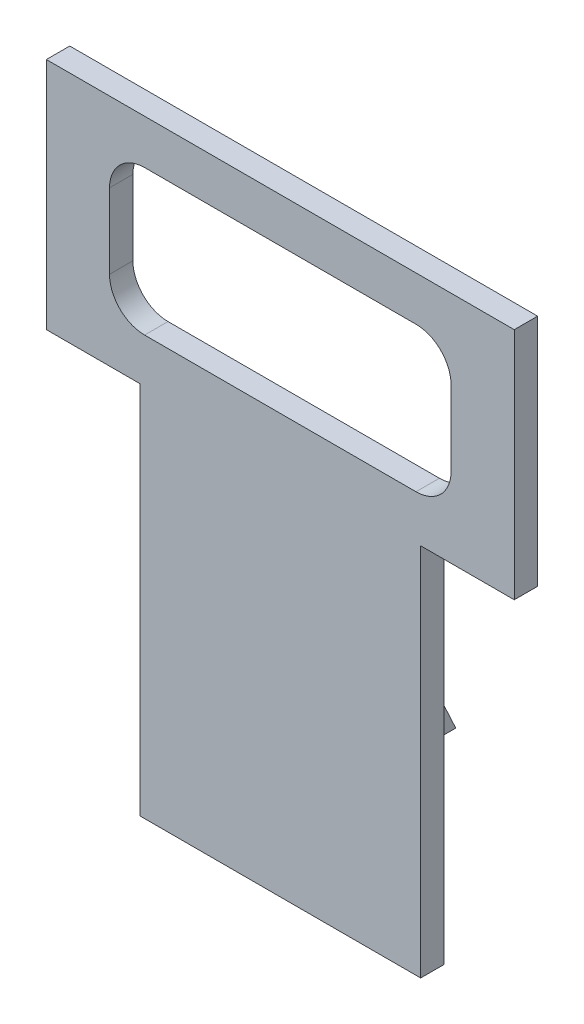
SolidWorks part; units mm, degrees
material "PVC 0.007 Plasticized"
ref_plane "Front Plane" through (0, 0, 0) normal (0, 0, 1) x (1, 0, 0)
ref_plane "Top Plane" through (0, 0, 0) normal (0, 1, 0) x (1, 0, 0)
ref_plane "Right Plane" through (0, 0, 0) normal (1, 0, 0) x (0, 0, -1)
sketch "Sketch1" plane through (0, 0, 0) normal (0, 0, 1) x (1, 0, 0)
  line L1 (0, 0) -> (100, 0)
  line L2 (0, 0) -> (0, 50)
  line L3 (0, 50) -> (100, 50)
  line L4 (100, 0) -> (100, 50)
  dimension "D1" = 100
  dimension "D2" = 50
extrude "Boss-Extrude1" add sketch "Sketch1" along normal blind 5
sketch "Sketch2" plane through (0, 0, 5) normal (0, 0, 1) x (1, 0, 0)
  line L0 (0, 50) -> (0, 0) construction
  line L1 (21, 40.5) -> (79, 40.5)
  line L2 (13.5, 33) -> (13.5, 17)
  line L3 (21, 9.5) -> (79, 9.5)
  line L4 (86.5, 33) -> (86.5, 17)
  line L5 (100, 50) -> (0, 50) construction
  arc A0 (21, 40.5) -> (13.5, 33) centre (21, 33) ccw
  arc A1 (13.5, 17) -> (21, 9.5) centre (21, 17) ccw
  arc A2 (86.5, 33) -> (79, 40.5) centre (79, 33) ccw
  arc A3 (79, 9.5) -> (86.5, 17) centre (79, 17) ccw
  dimension "D5" = 15
  dimension "D6" = 15
  dimension "D7" = 15
  dimension "D8" = 15
  dimension "D9" = 7.5
  dimension "D10" = 7.5
  dimension "D11" = 7.5
  dimension "D12" = 7.5
  dimension "D13" = 7.5
  dimension "D14" = 7.5
  dimension "D15" = 7.5
  dimension "D16" = 7.5
  dimension "D3" = 13.5
  dimension "D4" = 9.5
extrude "Cut-Extrude1" cut sketch "Sketch2" against normal blind 5
sketch "Sketch3" plane through (0, 0, 0) normal (0, -1, 0) x (1, 0, 0)
  line L0 (0, 5) -> (100, 5) construction
  line L1 (20, 5) -> (80, 5)
  line L2 (20, 5) -> (20, 0)
  line L3 (20, 0) -> (80, 0)
  line L4 (80, 5) -> (80, 0)
  line L5 (0, 0) -> (100, 0) construction
  line L6 (0, 5) -> (0, 0) construction
  line L7 (100, 5) -> (100, 0) construction
  dimension "D1" = 20
  dimension "D2" = 20
extrude "Boss-Extrude2" add sketch "Sketch3" along normal blind 80
sketch "Sketch6" plane through (0, 0, 0) normal (0, 0, -1) x (-1, 0, 0)
  line L0 (-80, -80) -> (-80, 0) construction
  line L1 (-52.5, 0) -> (-47.5, 0)
  line L2 (-52.5, 0) -> (-52.5, -65)
  line L3 (-52.5, -65) -> (-47.5, -65)
  line L4 (-47.5, 0) -> (-47.5, -65)
  line L5 (-20, -80) -> (-20, 0) construction
  line L6 (-20, -80) -> (-80, -80) construction
  dimension "D1" = 27.5
  dimension "D2" = 27.5
  dimension "D3" = 15
extrude "Boss-Extrude4" add sketch "Sketch6" along normal blind 30
sketch "Sketch7" plane through (52.5, 0, 0) normal (1, 0, 0) x (0, 0, -1)
  line L0 (0, 0) -> (30, -65)
  line L1 (0, 0) -> (30, 0)
  line L2 (30, 0) -> (30, -65)
extrude "Cut-Extrude3" cut sketch "Sketch7" against normal blind 5
